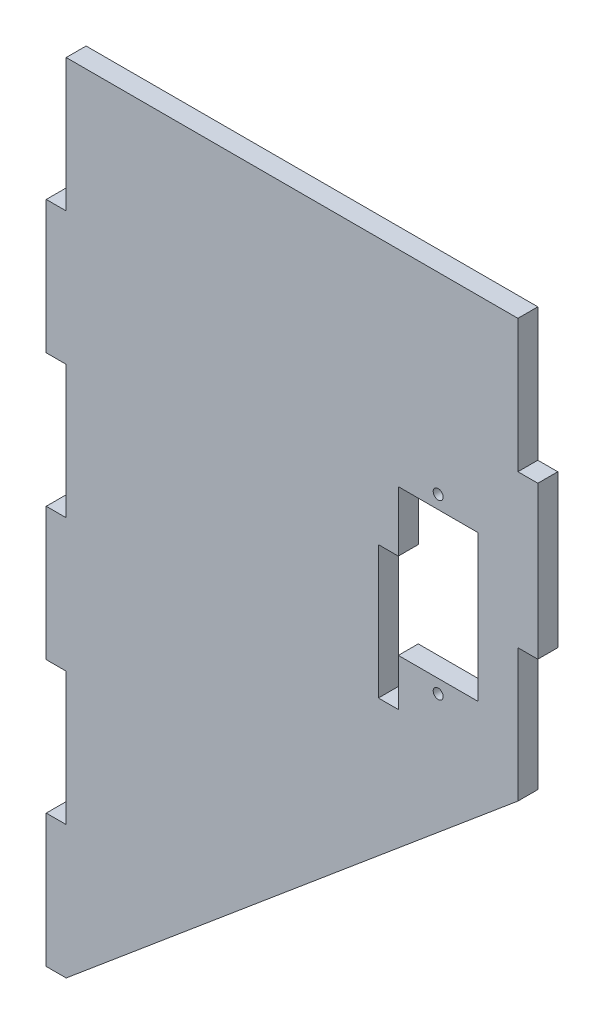
SolidWorks part; units mm, degrees
material "Acrilico TEC"
ref_plane "Front Plane" through (0, 0, 0) normal (0, 0, 1) x (1, 0, 0)
ref_plane "Top Plane" through (0, 0, 0) normal (0, 1, 0) x (1, 0, 0)
ref_plane "Right Plane" through (0, 0, 0) normal (1, 0, 0) x (0, 0, -1)
sketch "Sketch1" plane through (0, 0, 0) normal (0, 0, 1) x (1, 0, 0)
  line L0 (-3, 60) -> (-3, 40)
  line L1 (-3, 40) -> (0, 40)
  line L2 (0, 40) -> (0, 20)
  line L3 (0, 20) -> (-3, 20)
  line L4 (-3, 20) -> (-3, 0)
  line L5 (-3, 60) -> (0, 60)
  line L6 (0, 60) -> (0, 80)
  line L7 (0, 80) -> (-3, 80)
  line L8 (-3, 80) -> (-3, 100)
  line L9 (0, 120) -> (23.5, 120)
  line L10 (23.5, 120) -> (23.5, 105) construction
  line L11 (-3, 0) -> (0, 0)
  line L12 (23.5, 120) -> (68, 120)
  line L13 (68, 57.0588) -> (68, 77.0588)
  line L14 (47, 80) -> (50, 80)
  line L15 (47, 60) -> (47, 80)
  line L16 (50, 60) -> (47, 60)
  line L17 (68, 77.0588) -> (71, 77.0588)
  line L18 (71, 77.0588) -> (71, 100)
  line L19 (71, 100) -> (68, 100)
  line L20 (68, 100) -> (68, 120)
  line L21 (50, 89.0588) -> (62, 89.0588)
  line L22 (0, 0) -> (68, 57.0588)
  line L23 (0, 0) -> (3.8747, 0) construction
  line L24 (50, 89.0588) -> (50, 80)
  line L25 (50, 60) -> (50, 67.0588)
  line L26 (50, 67.0588) -> (62, 67.0588)
  line L27 (-3, 100) -> (0, 100)
  line L28 (0, 100) -> (0, 120)
  line L29 (56, 89.0588) -> (56, 91.0588) construction
  line L30 (62, 89.0588) -> (62, 67.0588)
  line L31 (62, 78.0588) -> (47, 78.0588) construction
  circle A0 centre (56, 91.0588) radius 0.75
  circle A1 centre (56, 65.0588) radius 0.75
  dimension "D19" = 1.5
  dimension "D2" = 12
  dimension "D3" = 20
  dimension "D4" = 23.5
  dimension "D5" = 20
  dimension "D6" = 3
  dimension "D7" = 22.9412
  dimension "D8" = 23.5
  dimension "D9" = 15
  dimension "D10" = 20
  dimension "D11" = 20
  dimension "D12" = 52.9412
  dimension "D13" = 40
  dimension "D14" = 20
  dimension "D15" = 3
  dimension "D16" = 22
  dimension "D17" = 3
  dimension "D18" = 2
  dimension "D20" = 40
extrude "Boss-Extrude1" add sketch "Sketch1" along normal blind 3
